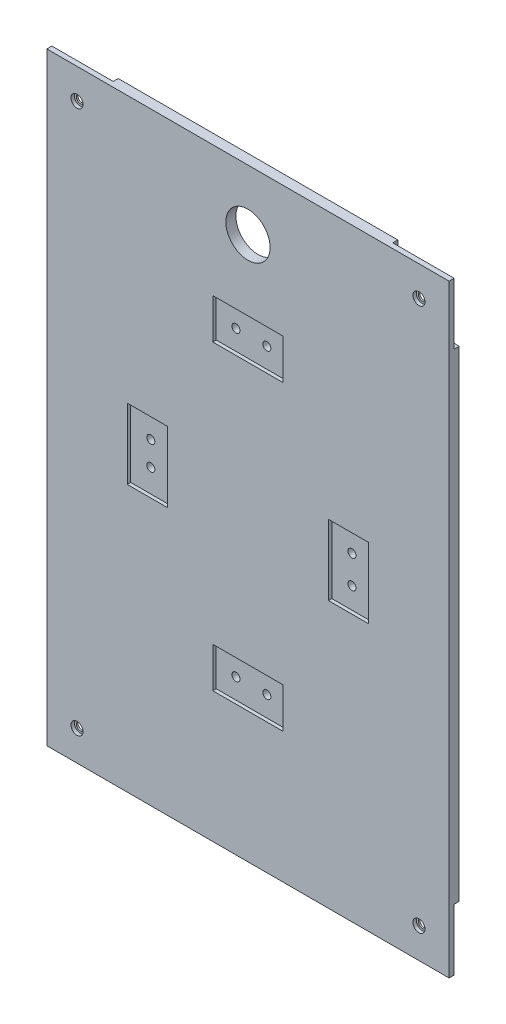
SolidWorks part; units mm, degrees
ref_plane "Alzado" through (0, 0, 0) normal (0, 0, 1) x (1, 0, 0)
ref_plane "Planta" through (0, 0, 0) normal (0, 1, 0) x (1, 0, 0)
ref_plane "Vista lateral" through (0, 0, 0) normal (1, 0, 0) x (0, 0, -1)
sketch "Croquis1" plane through (0, 0, 0) normal (0, 0, 1) x (1, 0, 0)
  line L1 (-100, -150) -> (100, -150)
  line L2 (-100, -150) -> (-100, 150)
  line L3 (-100, 150) -> (100, 150)
  line L4 (100, -150) -> (100, 150)
  line L5 (-100, -150) -> (100, 150) construction
  line L6 (-100, 150) -> (100, -150) construction
  point P0 (0, 0)
  dimension "D1" = 200
  dimension "D2" = 300
extrude "Saliente-Extruir1" add sketch "Croquis1" along normal blind 5
sketch "Croquis2" plane through (0, 0, 5) normal (0, 0, 1) x (1, 0, 0)
  line L0 (-100, 150) -> (0, 150) construction
  line L1 (100, 150) -> (-100, 150) construction
  line L2 (0, 150) -> (0, 120) construction
  circle A0 centre (0, 120) radius 11
  dimension "D2" = 22
  dimension "D1" = 30
extrude "Cortar-Extruir1" cut sketch "Croquis2" against normal blind 15
sketch "Croquis3" plane through (0, 0, 5) normal (0, 0, 1) x (1, 0, 0)
  line L0 (-100, 150) -> (-70, 150) construction
  line L1 (100, 150) -> (-100, 150) construction
  line L2 (100, 150) -> (-100, 150) construction
  line L3 (-100, 150) -> (-100, -150) construction
  line L4 (-100, 150) -> (0, 150) construction
  line L5 (0, 150) -> (0, 0) construction
  line L6 (100, -150) -> (100, 150) construction
  line L7 (85, 135) -> (100, 135) construction
  line L8 (-85, 135) -> (-100, 135) construction
  line L11 (-85, 150) -> (-100, 150) construction
  circle A1 centre (85, 135) radius 2
  circle A5 centre (-85, 135) radius 2
  circle A6 centre (-85, -135) radius 2
  circle A7 centre (85, -135) radius 2
  dimension "D3" = 2
  dimension "D6" = 15
  dimension "D4" = 170
  dimension "D1" = 30
  dimension "D2" = 2
  dimension "D5" = 270
  dimension "D7" = 15
extrude "Ag. Columna" cut sketch "Croquis3" against normal blind 15
sketch "Croquis4" plane through (0, 0, 5) normal (0, 0, 1) x (1, 0, 0)
  line L0 (-100, 150) -> (0, 150) construction
  line L1 (100, 150) -> (-100, 150) construction
  line L2 (0, 0) -> (50, 0) construction
  line L3 (0, 0) -> (0, 150) construction
  line L5 (50, 0) -> (50, 7) construction
  line L6 (-7.6684, 75) -> (-7.6684, 150) construction
  line L7 (0, 0) -> (-100, 0) construction
  line L8 (-100, 150) -> (-100, -150) construction
  circle A8 centre (-50, 6) radius 2
  circle A9 centre (-50, -6) radius 2
  circle A10 centre (50, -7) radius 2
  circle A11 centre (50, 7) radius 2
  circle A12 centre (-7.6684, 75) radius 2
  circle A13 centre (7.6684, 75) radius 2
  circle A14 centre (-7.6684, -75) radius 2
  circle A15 centre (7.6684, -75) radius 2
  point P19 (-110, 0)
  dimension "D3" = 75
  dimension "D2" = 4
  dimension "D1" = 4
  dimension "D6" = 4
  dimension "D7" = 4
  dimension "D5" = 6
  dimension "D8" = 7
extrude "Cortar-Extruir3" cut sketch "Croquis4" against normal blind 15
sketch "Croquis5" plane through (0, 0, 5) normal (0, 0, 1) x (1, 0, 0)
  line L0 (-50, 0) -> (-100, 0) construction
  line L1 (0, 0) -> (0, 82.3066) construction
  line L6 (-60, -17.5) -> (-40, -17.5)
  line L7 (-60, -17.5) -> (-60, 17.5)
  line L12 (17.5, -65.0704) -> (17.5, -85.0704)
  line L13 (-60, 17.5) -> (-40, 17.5)
  line L18 (-17.5, 65.0704) -> (17.5, 65.0704)
  line L19 (-17.5, 65.0704) -> (-17.5, 85.0704)
  line L24 (-40, -17.5) -> (-40, 17.5)
  line L25 (-60, -17.5) -> (-40, 17.5) construction
  line L26 (-60, 17.5) -> (-40, -17.5) construction
  line L27 (-100, 150) -> (-100, -150) construction
  line L28 (-50, 0) -> (0, 0) construction
  line L29 (40, -17.5) -> (40, 17.5)
  line L30 (60, -17.5) -> (40, -17.5)
  line L31 (60, -17.5) -> (60, 17.5)
  line L32 (60, 17.5) -> (40, 17.5)
  line L33 (-17.5, 85.0704) -> (17.5, 85.0704)
  line L34 (17.5, 65.0704) -> (17.5, 85.0704)
  line L35 (-17.5, 65.0704) -> (17.5, 85.0704) construction
  line L36 (-17.5, 85.0704) -> (17.5, 65.0704) construction
  line L37 (-17.5, -65.0704) -> (17.5, -65.0704)
  line L38 (-17.5, -65.0704) -> (-17.5, -85.0704)
  line L39 (-17.5, -85.0704) -> (17.5, -85.0704)
  circle A0 centre (-85, 135) radius 3
  circle A1 centre (85, 135) radius 3
  circle A2 centre (-85, -135) radius 3
  circle A3 centre (85, -135) radius 3
  point P0 (-50, 0)
  point P4 (-110, 0)
  point P15 (0, 75.0704)
  point P20 (0, -135)
  dimension "D5" = 6
  dimension "D1" = 20
  dimension "D2" = 35
  dimension "D3" = 20
  dimension "D4" = 35
extrude "Cortar-Extruir4" cut sketch "Croquis5" against normal blind 1.7
sketch "Croquis6" plane through (0, 0, 0) normal (0, 0, -1) x (-1, 0, 0)
  line L1 (-100, 150) -> (-69.5, 150)
  line L2 (-100, 150) -> (-100, 119.5)
  line L3 (-100, 119.5) -> (-69.5, 119.5)
  line L4 (-69.5, 150) -> (-69.5, 119.5)
  line L24 (100, 150) -> (69.5, 150)
  line L25 (100, 150) -> (100, 119.5)
  line L26 (100, 119.5) -> (69.5, 119.5)
  line L27 (69.5, 150) -> (69.5, 119.5)
  line L28 (100, -150) -> (69.5, -150)
  line L29 (100, -150) -> (100, -119.5)
  line L30 (100, -119.5) -> (69.5, -119.5)
  line L31 (69.5, -150) -> (69.5, -119.5)
  line L32 (-100, -150) -> (-69.5, -150)
  line L33 (-100, -150) -> (-100, -119.5)
  line L34 (-100, -119.5) -> (-69.5, -119.5)
  line L35 (-69.5, -150) -> (-69.5, -119.5)
  point P11 (0, 0)
  dimension "D1" = 30.5
  dimension "D2" = 30.5
extrude "Cortar-Extruir5" cut sketch "Croquis6" against normal blind 2.5
